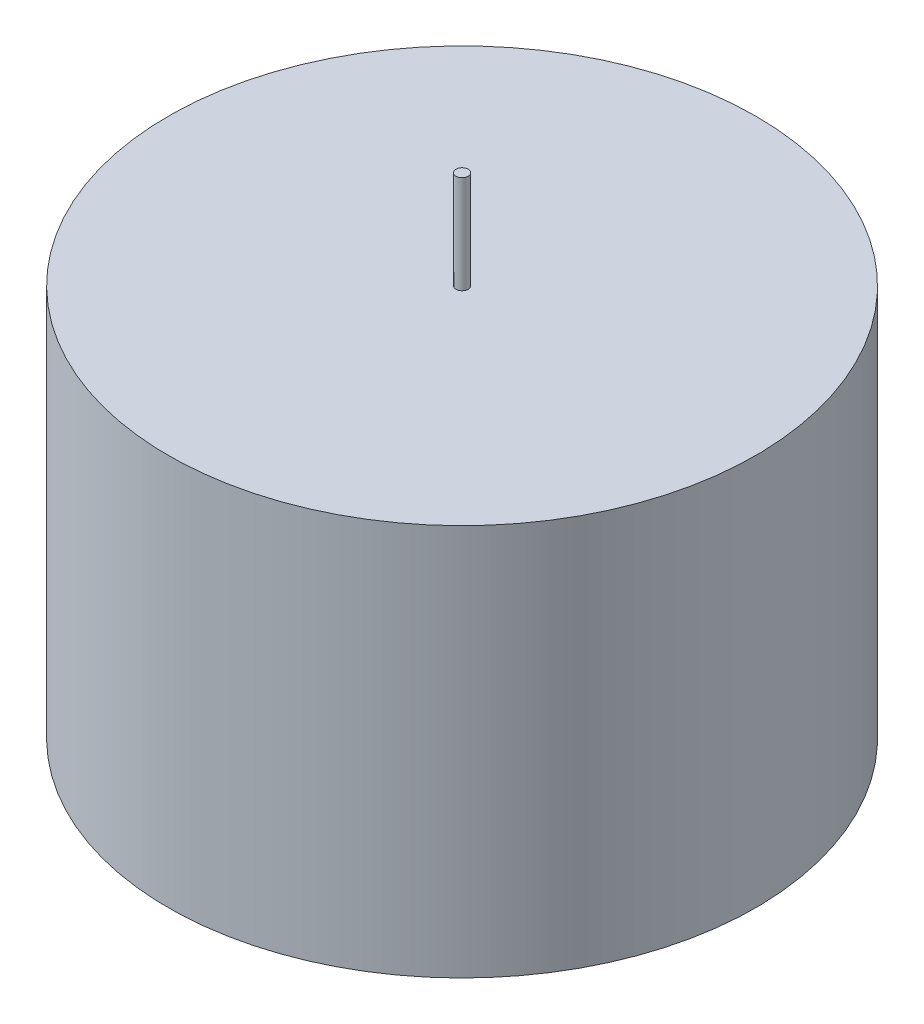
SolidWorks part; units mm, degrees
ref_plane "Front Plane" through (0, 0, 0) normal (0, 0, 1) x (1, 0, 0)
ref_plane "Top Plane" through (0, 0, 0) normal (0, 1, 0) x (1, 0, 0)
ref_plane "Right Plane" through (0, 0, 0) normal (1, 0, 0) x (0, 0, -1)
sketch "Sketch1" plane through (0, 0, 0) normal (0, 1, 0) x (1, 0, 0)
  circle A0 centre (0, 0) radius 457.2
  dimension "D1" = 914.4
extrude "Boss-Extrude1" add sketch "Sketch1" along normal blind 609.6
sketch "Sketch2" plane through (0, 609.6, 0) normal (0, 1, 0) x (1, 0, 0)
  circle A0 centre (0, 0) radius 9.525
  dimension "D1" = 19.05
extrude "Boss-Extrude2" add sketch "Sketch2" along normal blind 152.4 and the other way blind 762
